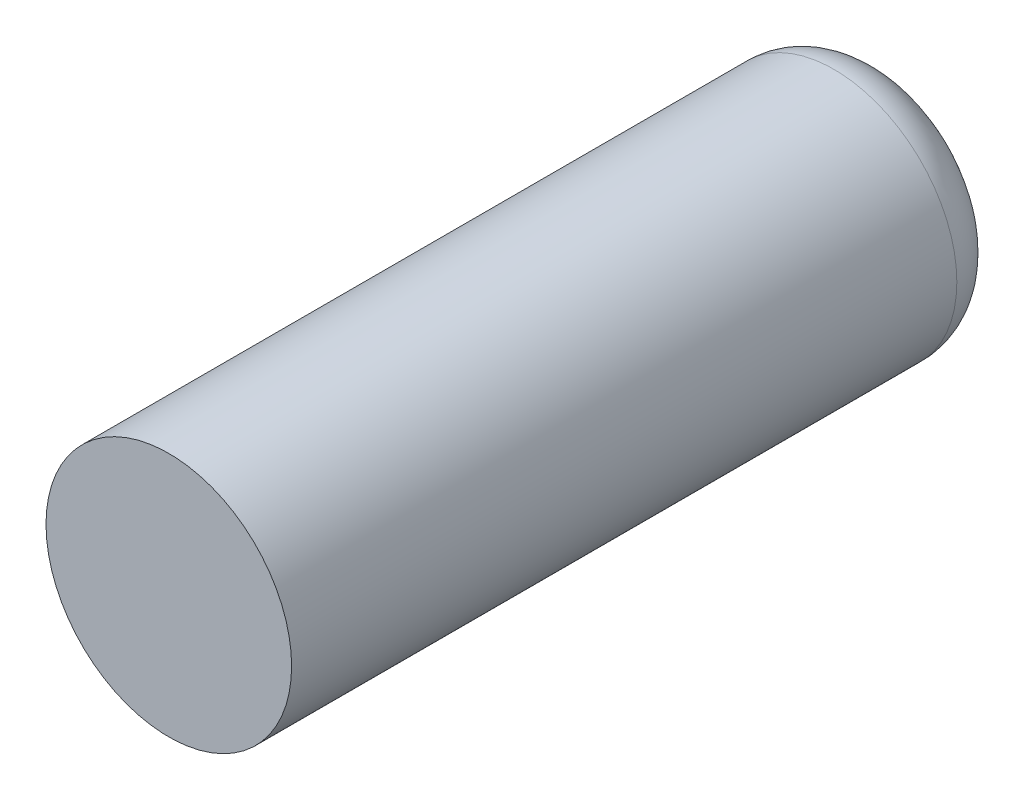
SolidWorks part; units mm, degrees
ref_plane "前视基准面" through (0, 0, 0) normal (0, 0, 1) x (1, 0, 0)
ref_plane "上视基准面" through (0, 0, 0) normal (0, 1, 0) x (1, 0, 0)
ref_plane "右视基准面" through (0, 0, 0) normal (1, 0, 0) x (0, 0, -1)
sketch "草图1" plane through (0, 0, 0) normal (0, 0, 1) x (1, 0, 0)
  circle A0 centre (0, 0) radius 2.4
  dimension "D1" = 4.8
extrude "凸台-拉伸1" add sketch "草图1" along normal blind 14
fillet "圆角1" radius 1 1 edges at (2.4, 0, 0)
